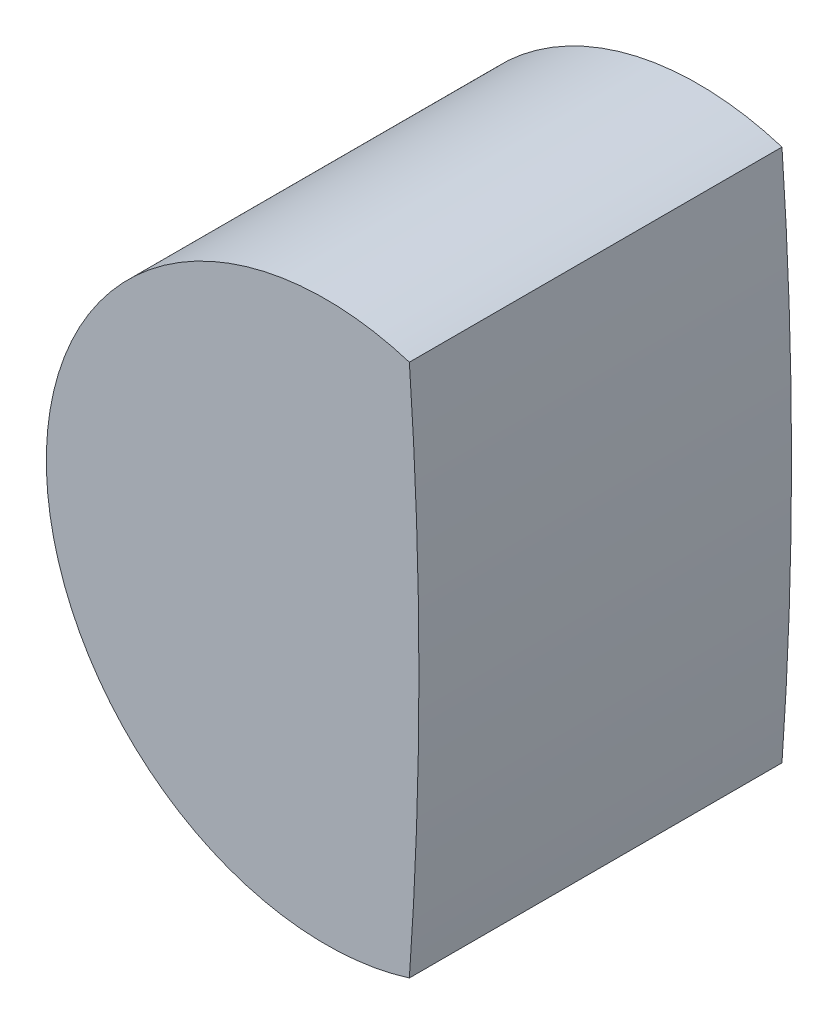
SolidWorks part; units mm, degrees
material "Acrylique (impact moyen-haut)"
ref_plane "Plan de face" through (0, 0, 0) normal (0, 0, 1) x (1, 0, 0)
ref_plane "Plan de dessus" through (0, 0, 0) normal (0, 1, 0) x (1, 0, 0)
ref_plane "Plan de droite" through (0, 0, 0) normal (1, 0, 0) x (0, 0, -1)
sketch "Esquisse1" plane through (0, 0, 0) normal (0, 0, 1) x (1, 0, 0)
  line L0 (0, 0) -> (-19.5, 0) construction
  arc A0 (0.4487, 1.4313) -> (0.4487, -1.4313) centre (0, 0) ccw
  arc A1 (0.4487, -1.4313) -> (0.4487, 1.4313) centre (-19.5, 0) ccw
  dimension "D1" = 3
  dimension "D3" = 40
  dimension "D2" = 19.5
extrude "Boss.-Extru.1" add sketch "Esquisse1" along normal blind 2
